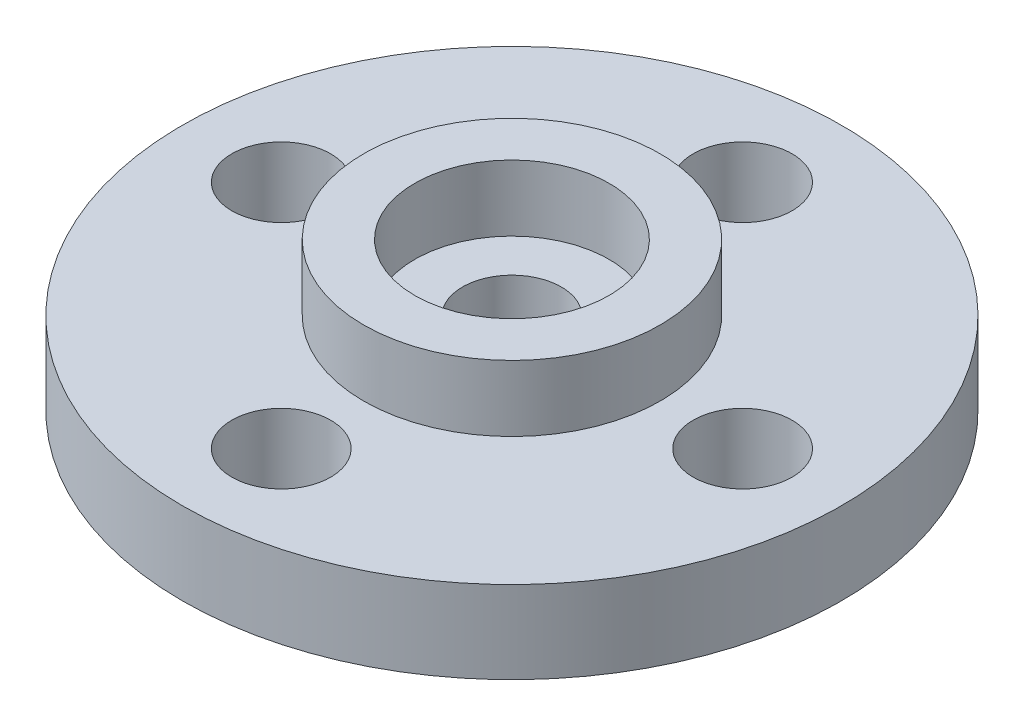
SolidWorks part; units mm, degrees
ref_plane "前视基准面" through (0, 0, 0) normal (0, 0, 1) x (1, 0, 0)
ref_plane "上视基准面" through (0, 0, 0) normal (0, 1, 0) x (1, 0, 0)
ref_plane "右视基准面" through (0, 0, 0) normal (1, 0, 0) x (0, 0, -1)
other "Configuration Table"
sketch "草图1" plane through (0, 0, 0) normal (0, 1, 0) x (1, 0, 0)
  circle A0 centre (0, 0) radius 1.5
  circle A1 centre (0, 0) radius 10
  circle A2 centre (0, 7) radius 1.5
  circle A3 centre (7, 0) radius 1.5
  circle A4 centre (0, -7) radius 1.5
  circle A5 centre (-7, 0) radius 1.5
  point P6 (-0.4162, -0.7502)
  point P8 (0, 0)
  point P9 (0, 0)
  point P15 (0, 0)
  point P16 (0, 0)
  dimension "D1" = 3
  dimension "D2" = 20
  dimension "D3" = 3
  dimension "D5" = 14
  dimension "D4" = 4
extrude "凸台-拉伸1" add sketch "草图1" along normal blind 2.5
sketch "草图2" plane through (0, 2.5, 0) normal (0, 1, 0) x (1, 0, 0)
  circle A0 centre (0, 0) radius 2.95
  circle A1 centre (0, 0) radius 4.5
  dimension "D1" = 5.9
  dimension "D2" = 9
extrude "凸台-拉伸2" add sketch "草图2" along normal blind 2
